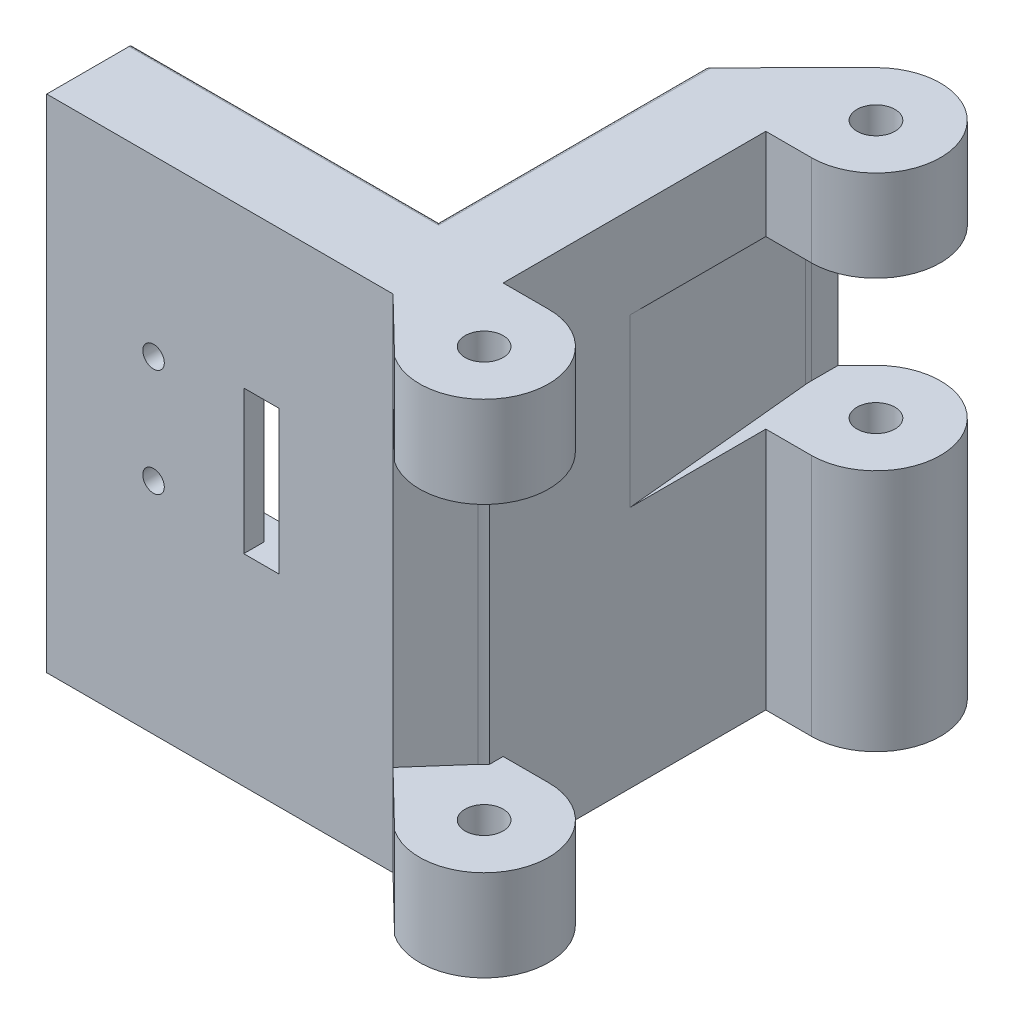
SolidWorks part; units mm, degrees
ref_plane "Front Plane" through (0, 0, 0) normal (0, 0, 1) x (1, 0, 0)
ref_plane "Top Plane" through (0, 0, 0) normal (0, 1, 0) x (1, 0, 0)
ref_plane "Right Plane" through (0, 0, 0) normal (1, 0, 0) x (0, 0, -1)
sketch "Sketch1" plane through (0, 0, 0) normal (0, 1, 0) x (1, 0, 0)
  line L0 (54.61, 0) -> (60.96, 0)
  line L1 (0, 0) -> (54.61, 0)
  line L2 (0, 0) -> (0, 54.61)
  line L3 (0, 54.61) -> (54.61, 54.61)
  line L4 (54.61, 0) -> (54.61, 54.61)
  line L5 (0, 54.61) -> (48.26, 54.61)
  line L6 (0, 54.61) -> (0, 6.35)
  line L7 (0, 6.35) -> (48.26, 6.35)
  line L8 (48.26, 54.61) -> (48.26, 6.35)
  line L9 (54.61, 54.61) -> (60.96, 54.61)
  line L10 (48.26, 54.61) -> (54.582, 60.9599)
  line L11 (60.96, 45.61) -> (54.61, 45.61)
  line L12 (60.96, 9) -> (54.61, 9)
  line L13 (48.26, 0) -> (55.9587, -7.4825)
  circle A0 centre (60.96, 0) radius 2.65
  circle A1 centre (60.96, 54.61) radius 2.65
  circle A2 centre (60.96, 0) radius 9
  circle A3 centre (60.96, 54.61) radius 9
  dimension "D7" = 5.3
  dimension "D8" = 5.3
  dimension "D9" = 6.35
  dimension "D10" = 6.35
  dimension "D1" = 54.61
  dimension "D2" = 54.61
  dimension "D3" = 6.35
  dimension "D4" = 6.35
  dimension "D5" = 6.35
  dimension "D6" = 6.35
extrude "Boss-Extrude1" add sketch "Sketch1" along normal blind 69.85
sketch "Sketch3" plane through (0, 0, 0) normal (-1, 0, 0) x (0, 0, 1)
  line L0 (-6.35, 69.85) -> (-6.35, 63.5)
  line L1 (-6.35, 69.85) -> (-6.35, 0) construction
  line L2 (-6.35, 63.5) -> (-12.7, 69.85)
  line L3 (-54.61, 69.85) -> (-6.35, 69.85) construction
  line L4 (-12.7, 69.85) -> (-6.35, 69.85)
  line L5 (-6.35, 0) -> (-6.35, 6.35)
  line L6 (-6.35, 69.85) -> (-6.35, 0) construction
  line L7 (-6.35, 6.35) -> (-12.7, 0)
  line L8 (-54.61, 0) -> (-6.35, 0) construction
  line L9 (-12.7, 0) -> (-6.35, 0)
  dimension "D1" = 6.35
  dimension "D2" = 6.35
  dimension "D3" = 6.35
  dimension "D4" = 6.35
extrude "Boss-Extrude2" add sketch "Sketch3" against normal up to next
sketch "Sketch4" plane through (0, 0, -6.35) normal (0, 0, -1) x (-1, 0, 0)
  line L0 (-48.26, 69.85) -> (-48.26, 63.5)
  line L1 (-48.26, 63.5) -> (-41.91, 69.85)
  line L2 (-41.91, 69.85) -> (-48.26, 69.85)
  line L6 (-48.26, 6.35) -> (-48.26, 0)
  line L7 (-48.26, 0) -> (-41.91, 0)
  line L8 (-48.26, 0) -> (0, 0) construction
  line L9 (-41.91, 0) -> (-48.26, 6.35)
  dimension "D1" = 6.35
  dimension "D2" = 6.35
extrude "Boss-Extrude3" add sketch "Sketch4" along normal up to surface (48.26 mm away)
sketch "Sketch7" plane through (0, 69.85, 0) normal (0, 1, 0) x (1, 0, 0)
  line L0 (54.61, 45.61) -> (54.61, 48.2321)
  line L1 (54.61, 45.61) -> (60.96, 45.61)
  line L2 (51.96, 54.61) -> (51.96, 58.3263)
  line L3 (41.91, 48.232) -> (54.582, 60.9599) construction
  line L4 (51.96, 58.3263) -> (54.582, 60.9599)
  line L5 (52.0014, 53.7474) -> (54.61, 26.6564)
  line L6 (54.61, 9) -> (54.61, 45.61) construction
  line L7 (54.61, 26.6564) -> (54.61, 45.61)
  circle A0 centre (60.96, 54.61) radius 9
  line M8 (54.61, 9) -> (54.61, 45.61)
  line M9 (54.61, 45.61) -> (60.96, 45.61)
  arc M10 (60.96, 45.61) -> (54.582, 60.9599) centre (60.96, 54.61) ccw
  line M11 (54.582, 60.9599) -> (41.91, 48.232)
  circle M13 centre (60.96, 54.61) radius 2.65
  dimension "D1" = 5.5
extrude "Cut-Extrude3" cut sketch "Sketch7" against normal blind 23.24 from offset 12.7 contours A0 M10 M13 | A0 L0 M9 | A0 L2 M11 | A0 L5 L0 M8 offset against normal yes
sketch "Sketch6" plane through (0, 0, 0) normal (0, -1, 0) x (-1, 0, 0)
  line L0 (-54.61, 9) -> (-54.61, 7.0995)
  line L1 (-48.26, 0) -> (-51.435, 0)
  line L2 (-48.26, 0) -> (-52.4514, -4.2814)
  line L3 (-54.61, 9) -> (-60.96, 9)
  line L4 (-48.26, 0) -> (-53.8163, 6.3002)
  circle A0 centre (-60.96, 0) radius 9.525
  line M7 (-54.61, 9) -> (-60.96, 9)
  arc M8 (-60.96, 9) -> (-55.9587, -7.4825) centre (-60.96, 0) ccw
  line M9 (-55.9587, -7.4825) -> (-48.26, 0)
  circle M13 centre (-60.96, 0) radius 2.65
  dimension "D1" = 19.05
extrude "Cut-Extrude2" cut sketch "Sketch6" against normal up to surface (44.45 mm away) from offset 12.7 contours A0 L3 M9 M8 | A0 L3 M9 M8 M13 | M13 | A0 L1 M9 | A0 L2 M9 | A0 L0 M7 | A0 L1 L4 offset against normal yes
fillet "Fillet1" radius 0.508 4 edges at (20.955, 69.85, -12.7) (41.91, 69.85, -30.466) (20.955, 0, -12.7) (41.91, 0, -30.466)
sketch "Sketch8" plane through (0, 0, -6.35) normal (0, 0, -1) x (-1, 0, 0)
  line L1 (-32.385, 28.1) -> (-12.385, 28.1)
  line L2 (-32.385, 28.1) -> (-32.385, 48.1)
  line L3 (-32.385, 48.1) -> (-12.385, 48.1)
  line L4 (-12.385, 28.1) -> (-12.385, 48.1)
  line L5 (-48.26, 63.5) -> (-48.26, 6.35) construction
  line L6 (-43.1364, 69.85) -> (0, 69.85) construction
  point P8 (-12.385, 38.1)
  dimension "D1" = 20
  dimension "D2" = 20
  dimension "D3" = 31.75
  dimension "D4" = 15.875
extrude "Cut-Extrude4" cut sketch "Sketch8" against normal blind 3.5
sketch "Sketch9" plane through (0, 0, 0) normal (0, 0, 1) x (1, 0, 0)
  line L0 (12.385, 48.1) -> (32.385, 48.1) construction
  line L1 (14.117, 29.832) -> (34.417, 29.832)
  line L2 (14.117, 29.832) -> (14.117, 50.132)
  line L3 (14.117, 50.132) -> (34.417, 50.132)
  line L4 (34.417, 29.832) -> (34.417, 50.132)
  line L6 (32.385, 48.1) -> (32.385, 28.1) construction
  dimension "D1" = 20.3
  dimension "D2" = 20.3
  dimension "D3" = 2.032
  dimension "D4" = 2.032
sketch "Sketch10" plane through (0, 0, -2.85) normal (0, 0, -1) x (-1, 0, 0)
  line L0 (-12.385, 28.1) -> (-12.385, 48.1) construction
  line L1 (-32.385, 28.1) -> (-12.385, 28.1) construction
  line L2 (-12.385, 48.1) -> (-32.385, 48.1) construction
  line L3 (-12.385, 48.1) -> (-32.385, 48.1) construction
  line L4 (-32.385, 28.1) -> (-27.4583, 28.1)
  line L5 (-32.385, 28.1) -> (-32.385, 48.1)
  line L6 (-32.385, 48.1) -> (-27.4583, 48.1)
  line L7 (-27.4583, 28.1) -> (-27.4583, 48.1)
  circle A0 centre (-14.885, 30.6) radius 1.5
  circle A1 centre (-14.885, 45.6) radius 1.5
  point P4 (-27.4583, 48.1)
  point P17 (-32.385, 28.1)
  dimension "D1" = 3
  dimension "D3" = 3
  dimension "D2" = 2.5
  dimension "D4" = 2.5
  dimension "2.5 mm" = 2.5
  dimension "D6" = 2.5
extrude "Cut-Extrude6" cut sketch "Sketch10" against normal through all both and the other way through all
